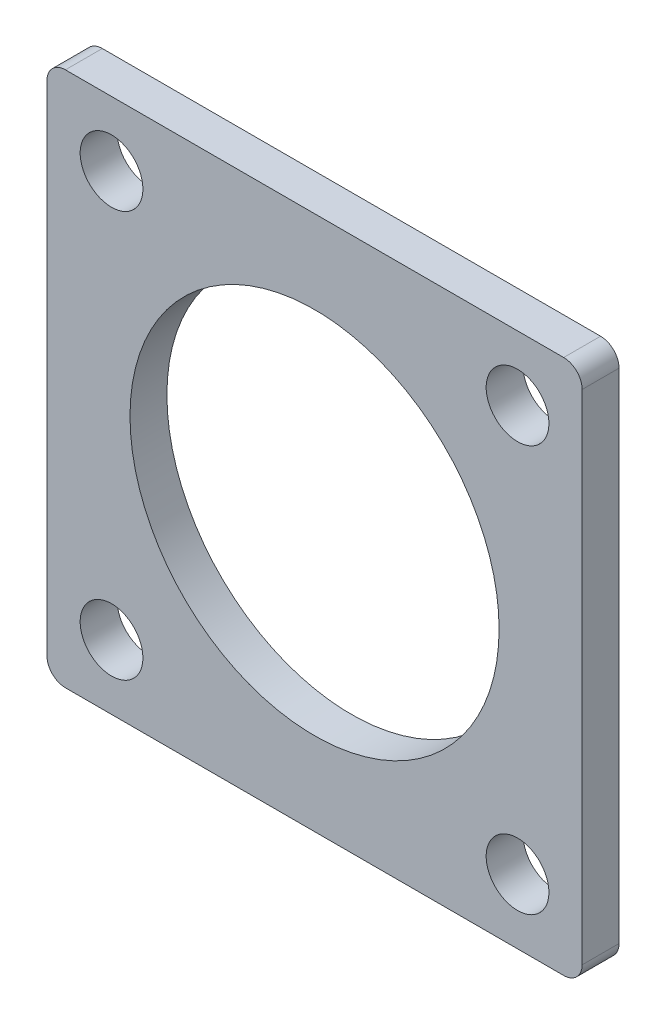
SolidWorks part; units mm, degrees
ref_plane "前视" through (0, 0, 0) normal (0, 0, 1) x (1, 0, 0)
ref_plane "上视" through (0, 0, 0) normal (0, 1, 0) x (1, 0, 0)
ref_plane "右视" through (0, 0, 0) normal (1, 0, 0) x (0, 0, -1)
sketch "草图1" plane through (0, 0, 0) normal (0, 0, 1) x (1, 0, 0)
  line L1 (-14.5, 14.5) -> (14.5, 14.5)
  line L2 (-14.5, 14.5) -> (-14.5, -14.5)
  line L3 (-14.5, -14.5) -> (14.5, -14.5)
  line L4 (14.5, 14.5) -> (14.5, -14.5)
  line L5 (-14.5, 14.5) -> (14.5, -14.5) construction
  line L6 (-14.5, -14.5) -> (14.5, 14.5) construction
  point P0 (0, 0)
  dimension "D1" = 29
  dimension "D2" = 29
extrude "凸台-拉伸1" add sketch "草图1" along normal blind 2
fillet "圆角1" radius 1 4 edges at (14.5, -14.5, 1) (-14.5, -14.5, 1) (14.5, 14.5, 1) (-14.5, 14.5, 1)
hole_wizard "M3 间隙孔1" positions "草图2" profile "草图3" hole size "M3" standard "GB"
sketch "草图2" plane through (0, 0, 2) normal (0, 0, 1) x (1, 0, 0)
  line L1 (-11, -11) -> (11, -11) construction
  line L2 (-11, -11) -> (-11, 11) construction
  line L3 (-11, 11) -> (11, 11) construction
  line L4 (11, -11) -> (11, 11) construction
  line L5 (-11, -11) -> (11, 11) construction
  line L6 (-11, 11) -> (11, -11) construction
  point P0 (-11, 11)
  point P2 (11, 11)
  point P102 (-11, -11)
  point P104 (11, -11)
  dimension "D1" = 22
  dimension "D2" = 22
  dimension "D3" = 11
  dimension "D4" = 11
sketch "草图3" plane through (-11, 11, 2) normal (1, 0, 0) x (0, -1, 0)
  line L0 (0, 0) -> (0, 8.5215)
  line L1 (0, 8.5215) -> (1.7, 7.5)
  line L2 (1.7, 7.5) -> (1.7, 0)
  line L5 (1.7, 0) -> (0, 0)
  line L10 (0, 8.5215) -> (-1.7, 7.5) construction
  line L11 (0, -6.35) -> (0, 107.95) construction
  dimension "孔直径" = 3.4
  dimension "孔深度" = 7.5
  dimension "导头角度" = 118
sketch "草图4" plane through (0, 0, 2) normal (0, 0, 1) x (1, 0, 0)
  circle A0 centre (0, 0) radius 10
  dimension "D1" = 20
extrude "切除-拉伸1" cut sketch "草图4" against normal through all
